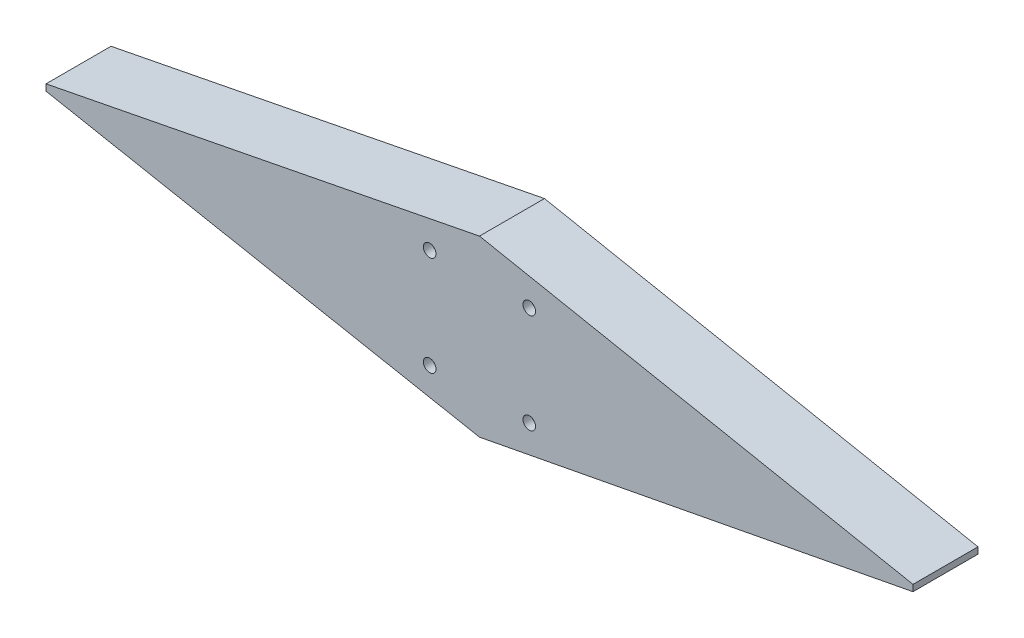
SolidWorks part; units mm, degrees
material "Custom Plastic"
ref_plane "Front Plane" through (0, 0, 0) normal (0, 0, 1) x (1, 0, 0)
ref_plane "Top Plane" through (0, 0, 0) normal (0, 1, 0) x (1, 0, 0)
ref_plane "Right Plane" through (0, 0, 0) normal (1, 0, 0) x (0, 0, -1)
sketch "Sketch1" plane through (0, 0, 0) normal (0, 0, 1) x (1, 0, 0)
  line L1 (100, -25) -> (-100, -25)
  line L2 (100, -25) -> (100, 25)
  line L3 (100, 25) -> (-100, 25)
  line L4 (-100, -25) -> (-100, 25)
  line L5 (100, -25) -> (-100, 25) construction
  line L6 (100, 25) -> (-100, -25) construction
  point P0 (0, 0)
  dimension "D1" = 50
  dimension "D2" = 200
extrude "Boss-Extrude1" add sketch "Sketch1" along normal mid plane 15
sketch "Sketch3" plane through (0, 0, 7.5) normal (0, 0, 1) x (1, 0, 0)
  line L0 (-11.4905, 11.4905) -> (11.4905, -11.4905) construction
  line L1 (-11.4905, -11.4905) -> (11.4905, 11.4905) construction
  point P0 (-11.4905, 11.4905)
  point P1 (11.4905, -11.4905)
  point P4 (11.4905, 11.4905)
  point P7 (-11.4905, -11.4905)
  dimension "D1" = 11.4905
  dimension "D2" = 11.4905
  dimension "D3" = 11.4905
  dimension "D4" = 11.4905
  dimension "D5" = 11.4905
  dimension "D6" = 11.4905
  dimension "D7" = 11.4905
  dimension "D8" = 11.4905
sketch "Sketch6" plane through (0, 0, -7.5) normal (0, 0, -1) x (-1, 0, 0)
  spline S0 degree 3 poles (413.2243, -930.7132) (366.5057, -134.4745) (181.0641, -55.097) (-14.5643, -17.1964) (-16.6477, -16.7981) (-20.8154, -16.0064) (-22.8994, -15.6113) (-33.321, -13.6437) (-41.6707, -12.1351) (-58.3677, -9.1065) (-66.7154, -7.5879) (-79.2181, -5.2084) (-83.3823, -4.3983) (-234.7583, 26.0228) (-375.9111, 85.5884) (-350.8144, 967.0552) knots -5.683973 -5.683973 -5.683973 -5.683973 0.125 0.125 0.1875 0.1875 0.25 0.25 0.5 0.5 0.75 0.75 0.875 0.875 5.299692 5.299692 5.299692 5.299692 only from (0, -20.0854) to (-100, -0.9654) construction
  spline S1 degree 3 poles (352.1854, 966.7091) (375.8766, 85.5629) (234.7158, 26.0142) (83.3822, -4.3983) (79.2181, -5.2084) (66.7156, -7.5878) (58.3678, -9.1065) (41.6709, -12.1351) (33.3213, -13.6436) (22.8996, -15.6112) (20.8155, -16.0064) (16.6477, -16.798) (14.5643, -17.1964) (-181.1541, -55.1145) (-366.5977, -134.5329) (-411.7839, -931.3559) knots -4.298436 -4.298436 -4.298436 -4.298436 0.125 0.125 0.25 0.25 0.5 0.5 0.75 0.75 0.8125 0.8125 0.875 0.875 6.686615 6.686615 6.686615 6.686615 only from (100, -0.9654) to (0, -20.0854) construction
  spline S2 degree 3 poles (-416.2553, 929.3322) (-369.9116, 135.4632) (-182.7514, 56.0244) (16.651, 16.7402) (20.8203, 15.9376) (33.3294, 13.5345) (41.6808, 11.9947) (58.3795, 8.8957) (66.7274, 7.3378) (79.2277, 4.8897) (83.3909, 4.055) (235.6779, -27.5335) (376.8437, -91.3606) (346.9001, -968.5172) knots -5.733287 -5.733287 -5.733287 -5.733287 0.125 0.125 0.25 0.25 0.5 0.5 0.75 0.75 0.875 0.875 5.328918 5.328918 5.328918 5.328918 only from (0, 20.0856) to (100, 0.5102) construction
  spline S3 degree 3 poles (-348.1774, -968.2028) (-376.8137, -91.3348) (-235.6367, -27.525) (-83.391, 4.055) (-79.2279, 4.8896) (-66.7274, 7.3378) (-58.3796, 8.8957) (-41.6809, 11.9947) (-33.3297, 13.5344) (-20.8205, 15.9376) (-16.6511, 16.7402) (182.7823, 56.0304) (369.9437, 135.483) (415.7608, 929.5497) knots -4.327736 -4.327736 -4.327736 -4.327736 0.125 0.125 0.25 0.25 0.5 0.5 0.75 0.75 0.875 0.875 6.734167 6.734167 6.734167 6.734167 only from (-100, 0.5102) to (0, 20.0856) construction
  spline S4 degree 3 poles (0, -20.0854) (-4.156, -19.233) (-8.3171, -18.4067) (-14.5643, -17.1964) (-16.6477, -16.7981) (-20.8154, -16.0064) (-22.8994, -15.6113) (-33.321, -13.6437) (-41.6707, -12.1351) (-58.3677, -9.1065) (-66.7154, -7.5879) (-79.2181, -5.2084) (-83.3823, -4.3983) (-91.7002, -2.7267) (-95.8543, -1.867) (-100, -0.9654) knots 0 0 0 0 0.125 0.125 0.1875 0.1875 0.25 0.25 0.5 0.5 0.75 0.75 0.875 0.875 1 1 1 1
  spline S5 degree 3 poles (100, -0.9654) (95.8542, -1.867) (91.7001, -2.7267) (83.3822, -4.3983) (79.2181, -5.2084) (66.7156, -7.5878) (58.3678, -9.1065) (41.6709, -12.1351) (33.3213, -13.6436) (22.8996, -15.6112) (20.8155, -16.0064) (16.6477, -16.798) (14.5643, -17.1964) (8.317, -18.4067) (4.156, -19.233) (0, -20.0854) knots 0 0 0 0 0.125 0.125 0.25 0.25 0.5 0.5 0.75 0.75 0.8125 0.8125 0.875 0.875 1 1 1 1
  spline S6 degree 3 poles (0, 20.0856) (4.1572, 19.221) (8.3193, 18.3816) (16.651, 16.7402) (20.8203, 15.9376) (33.3294, 13.5345) (41.6808, 11.9947) (58.3795, 8.8957) (66.7274, 7.3378) (79.2277, 4.8897) (83.3909, 4.055) (91.7055, 2.3303) (95.8573, 1.4419) (100, 0.5102) knots 0 0 0 0 0.125 0.125 0.25 0.25 0.5 0.5 0.75 0.75 0.875 0.875 1 1 1 1
  spline S7 degree 3 poles (-100, 0.5102) (-95.8573, 1.4419) (-91.7055, 2.3303) (-83.391, 4.055) (-79.2279, 4.8896) (-66.7274, 7.3378) (-58.3796, 8.8957) (-41.6809, 11.9947) (-33.3297, 13.5344) (-20.8205, 15.9376) (-16.6511, 16.7402) (-8.3193, 18.3816) (-4.1572, 19.221) (0, 20.0856) knots 0 0 0 0 0.125 0.125 0.25 0.25 0.5 0.5 0.75 0.75 0.875 0.875 1 1 1 1
sketch "Sketch15" plane through (0, 0, -7.5) normal (0, 0, -1) x (-1, 0, 0)
  line L0 (-100, 0.5102) -> (-100, 25)
  line L1 (-100, 25) -> (100, 25)
  line L2 (100, 25) -> (100, 0.5102)
  line L3 (100, 0.5102) -> (0, 20.0856)
  line L4 (0, 20.0856) -> (-100, 0.5102)
  line L5 (-100, -0.9654) -> (-100, -25)
  line L6 (-100, -25) -> (100, -25)
  line L7 (100, -25) -> (100, -0.9654)
  line L8 (100, 25) -> (100, -25) construction
  line L9 (100, -0.9654) -> (0, -20.0854)
  line L10 (0, -20.0854) -> (-100, -0.9654)
  point P14 (0, -20.0854)
  point P22 (100, -2.4023)
  point P23 (100, -0.9654)
  dimension "D1" = 1.4756
extrude "Cut-Extrude1" cut sketch "Sketch15" against normal through all
shell "Shell2" thickness 2
hole_wizard "Ø20.0mm Dowel Hole1" positions "Sketch3" profile "Sketch16" hole size "Ø20.0" standard "ANSI Metric" end condition through all
sketch "Sketch16" plane through (-11.4905, 11.4905, 7.5) normal (1, 0, 0) x (0, -1, 0)
  line L0 (0, 0) -> (0, 15)
  line L1 (0, 15) -> (1.45, 15)
  line L2 (1.45, 15) -> (1.45, 0)
  line L5 (1.45, 0) -> (0, 0)
  line L11 (0, -6.35) -> (0, 107.95) construction
  dimension "Thru Hole Dia." = 2.9
  dimension "Thru Hole Depth" = 15
